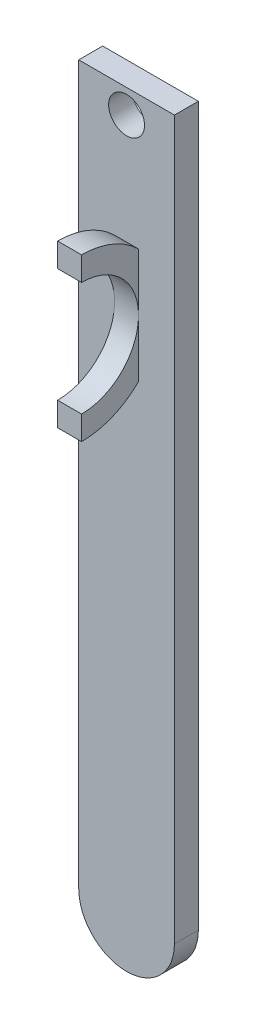
SolidWorks part; units mm, degrees
ref_plane "Front Plane" through (0, 0, 0) normal (0, 0, 1) x (1, 0, 0)
ref_plane "Top Plane" through (0, 0, 0) normal (0, 1, 0) x (1, 0, 0)
ref_plane "Right Plane" through (0, 0, 0) normal (1, 0, 0) x (0, 0, -1)
sketch "Sketch1" plane through (0, 0, 0) normal (0, 0, 1) x (1, 0, 0)
  line L1 (-20, 160) -> (20, 160)
  line L2 (-20, 160) -> (-20, -160)
  line L3 (-20, -160) -> (20, -160)
  line L4 (20, 160) -> (20, -160)
  circle A1 centre (0, -140) radius 20
  point P4 (-20, 0)
  point P5 (0, -160)
  dimension "D1" = 320
  dimension "D2" = 40
extrude "Boss-Extrude2" add sketch "Sketch1" along normal blind 10 contours A1 L4 L1 L2 | A1 L1
sketch "Sketch2" plane through (0, 0, 0) normal (0, 0, -1) x (-1, 0, 0)
  line L1 (20, 160) -> (-20, 160) construction
  circle A0 centre (0, 150) radius 7.5
  point P2 (0, 0)
  point P4 (0, 116.3087)
  point P5 (0, 113.5348)
  dimension "D1" = 15
  dimension "D2" = 10
extrude "Cut-Extrude2" cut sketch "Sketch2" against normal blind 10 contours A0
sketch "Sketch3" plane through (0, 0, 0) normal (1, 0, 0) x (0, 0, -1)
  line L0 (-33.8088, 113.8088) -> (-33.8088, 103.8088)
  line L1 (-33.8088, 56.1912) -> (-33.8088, 46.1912)
  line L2 (-10, 160) -> (-10, -140) construction
  line L3 (0, 160) -> (0, -140) construction
  arc A0 (-33.8088, 56.1912) -> (-33.8088, 103.8088) centre (-33.8088, 80) ccw
  arc A1 (-33.8088, 46.1912) -> (-33.8088, 113.8088) centre (-33.8088, 80) ccw
  point P1 (-34.1881, 80.42)
  point P10 (-33.8088, 53.681)
  dimension "D1" = 80
extrude "elbow motor holder" add sketch "Sketch3" along normal mid plane 10
